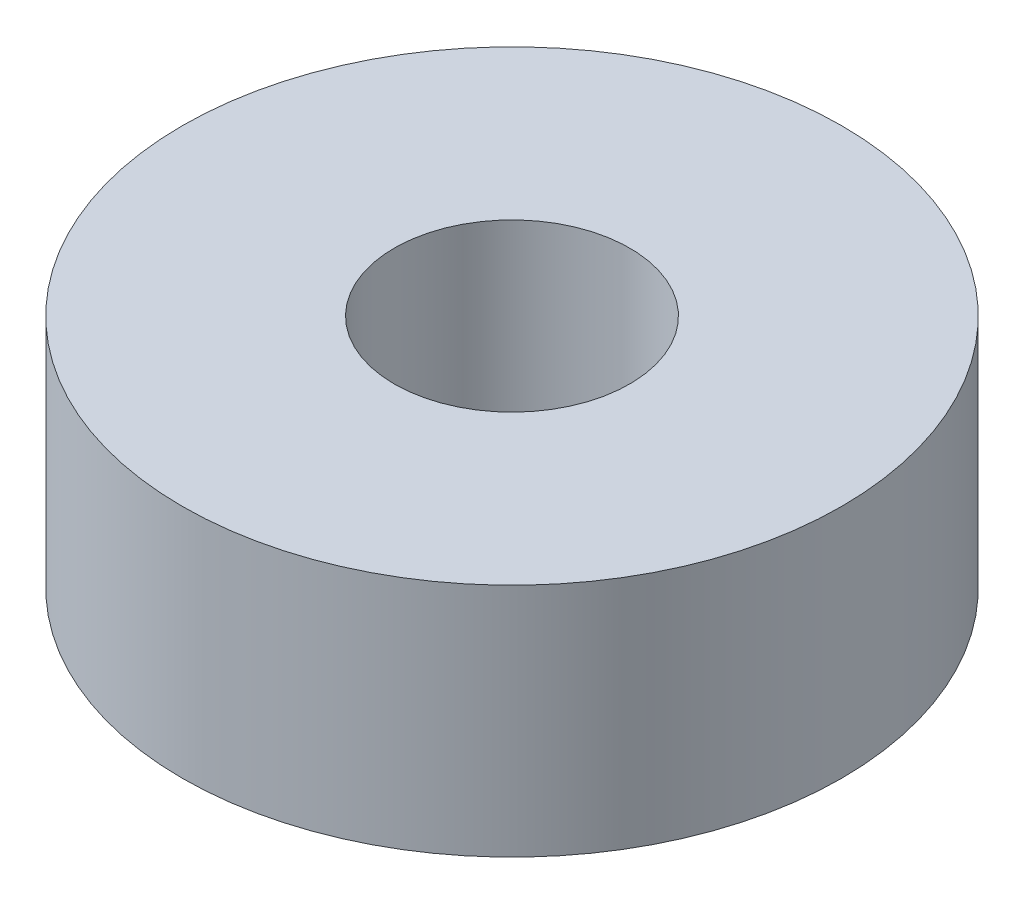
SolidWorks part; units mm, degrees
material "1060 Alloy"
ref_plane "Front Plane" through (0, 0, 0) normal (0, 0, 1) x (1, 0, 0)
ref_plane "Top Plane" through (0, 0, 0) normal (0, 1, 0) x (1, 0, 0)
ref_plane "Right Plane" through (0, 0, 0) normal (1, 0, 0) x (0, 0, -1)
sketch "Sketch1" plane through (0, 0, 0) normal (0, 1, 0) x (1, 0, 0)
  circle A0 centre (0, 0) radius 7
  dimension "D1" = 14
extrude "Boss-Extrude1" add sketch "Sketch1" along normal mid plane 5
sketch "Sketch2" plane through (0, 2.5, 0) normal (0, 1, 0) x (1, 0, 0)
  circle A0 centre (0, 0) radius 2.5
  dimension "D1" = 5
extrude "Cut-Extrude1" cut sketch "Sketch2" against normal up to next
